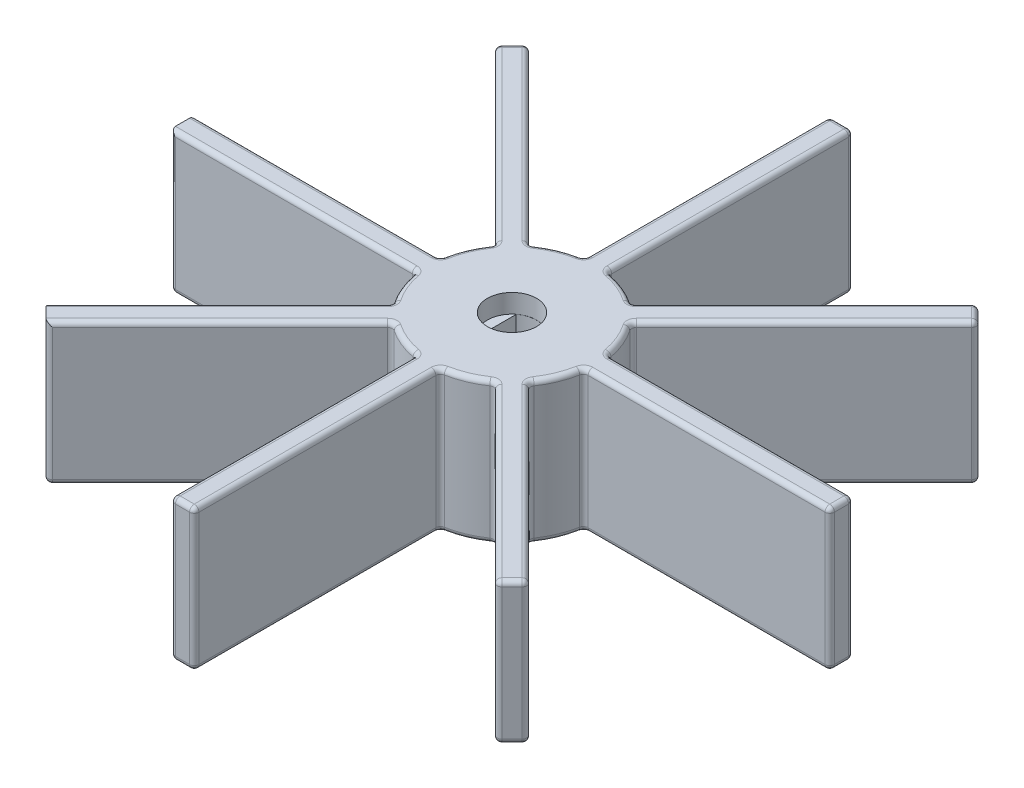
SolidWorks part; units mm, degrees
ref_plane "Front Plane" through (0, 0, 0) normal (0, 0, 1) x (1, 0, 0)
ref_plane "Top Plane" through (0, 0, 0) normal (0, 1, 0) x (1, 0, 0)
ref_plane "Right Plane" through (0, 0, 0) normal (1, 0, 0) x (0, 0, -1)
sketch "Sketch1" plane through (0, 0, 0) normal (0, 1, 0) x (1, 0, 0)
  line L0 (1.6, -2.0494) -> (1.6, 2.0494)
  line L1 (-1.6, -2.0494) -> (-1.6, 2.0494)
  line L2 (1.6, -2.0494) -> (-1.6, -2.0494) construction
  line L3 (1.6, 2.0494) -> (-1.6, 2.0494) construction
  circle A0 centre (0, 0) radius 9
  arc A1 (1.6, 2.0494) -> (-1.6, 2.0494) centre (0, 0) ccw
  arc A2 (-1.6, -2.0494) -> (1.6, -2.0494) centre (0, 0) ccw
  dimension "D1" = 18
  dimension "D2" = 5.2
  dimension "D3" = 3.2
extrude "Boss-Extrude1" add sketch "Sketch1" along normal blind 15
sketch "Sketch4" plane through (0, 0, 0) normal (0, 1, 0) x (1, 0, 0)
  line L0 (35, 0) -> (8, 0) construction
  line L2 (8, -1.25) -> (35, -1.25)
  line L3 (8, -1.25) -> (8, 1.25)
  line L4 (8, 1.25) -> (35, 1.25)
  line L5 (35, -1.25) -> (35, 1.25)
  dimension "D1" = 0
  dimension "D2" = 8
  dimension "D3" = 2.5
  dimension "D4" = 35
extrude "Boss-Extrude2" add sketch "Sketch4" along normal up to surface (15 mm away) up to face at (0, 15, 9)
pattern_circular "CirPattern1" count 8 over 360 about axis through (0, 0, 0) along (0, 1, 0) of "Boss-Extrude2"
sketch "Sketch6" plane through (0, 15, 0) normal (0, 1, 0) x (1, 0, 0)
  circle A0 centre (0, 0) radius 2.61
  dimension "D1" = 5.22
extrude "Cut-Extrude2" cut sketch "Sketch6" against normal blind 2
fillet "Fillet1" radius 0.5 98 edges at (-35, 7.5, -1.25) (-35, 0, 0) (-21.9564, 15, -1.25) (-21.9564, 15, 1.25) (-3.4442, 0, 8.3149) (-3.4442, 15, 8.3149) (-7.1862, 7.5, 5.4184) (-16.4094, 0, 14.6416) (-14.6416, 0, 16.4094) (-5.4184, 7.5, 7.1862) (-23.8649, 7.5, 25.6326) (-25.6326, 7.5, 23.8649) (-24.7487, 0, 24.7487) (-16.4094, 15, 14.6416) (-14.6416, 15, 16.4094) (3.4442, 0, 8.3149) (3.4442, 15, 8.3149) (-1.25, 7.5, 8.9128) (-1.25, 0, 21.9564) (1.25, 0, 21.9564) (1.25, 7.5, 8.9128) (1.25, 7.5, 35) (-1.25, 7.5, 35) (0, 0, 35) (-1.25, 15, 21.9564) (0, 15, 35) (1.25, 15, 21.9564) (8.3149, 0, 3.4442) (8.3149, 15, 3.4442) (5.4184, 7.5, 7.1862) (14.6416, 0, 16.4094) (16.4094, 0, 14.6416) (7.1862, 7.5, 5.4184) (25.6326, 7.5, 23.8649) (23.8649, 7.5, 25.6326) (24.7487, 0, 24.7487) (14.6416, 15, 16.4094) (24.7487, 15, 24.7487) (16.4094, 15, 14.6416) (8.3149, 15, -3.4442) (8.3149, 0, -3.4442) (8.9128, 7.5, -1.25) (8.9128, 7.5, 1.25) (21.9564, 0, 1.25) (21.9564, 0, -1.25) (35, 7.5, -1.25) (35, 7.5, 1.25) (35, 0, 0) (21.9564, 15, 1.25) (35, 15, 0) (21.9564, 15, -1.25) (3.4442, 0, -8.3149) (3.4442, 15, -8.3149) (7.1862, 7.5, -5.4184) (16.4094, 0, -14.6416) (14.6416, 0, -16.4094) (5.4184, 7.5, -7.1862) (23.8649, 7.5, -25.6326) (25.6326, 7.5, -23.8649) (24.7487, 0, -24.7487) (16.4094, 15, -14.6416) (24.7487, 15, -24.7487) (14.6416, 15, -16.4094) (-3.4442, 0, -8.3149) (-3.4442, 15, -8.3149) (1.25, 7.5, -8.9128) (1.25, 0, -21.9564) (-1.25, 0, -21.9564) (-1.25, 7.5, -8.9128) (-1.25, 7.5, -35) (1.25, 7.5, -35) (0, 0, -35) (1.25, 15, -21.9564) (0, 15, -35) (-1.25, 15, -21.9564) (-8.3149, 0, -3.4442) (0, 0, 2.6) (-8.3149, 15, -3.4442) (-5.4184, 7.5, -7.1862) (-14.6416, 0, -16.4094) (-16.4094, 0, -14.6416) (1.6, 0, 0) (-7.1862, 7.5, -5.4184) (-25.6326, 7.5, -23.8649) (-23.8649, 7.5, -25.6326) (-24.7487, 0, -24.7487) (-14.6416, 15, -16.4094) (-24.7487, 15, -24.7487) (-16.4094, 15, -14.6416) (0, 0, -2.6) (-1.6, 0, 0) (-8.3149, 0, 3.4442) (-8.3149, 15, 3.4442) (-8.9128, 7.5, -1.25) (-21.9564, 0, -1.25) (-21.9564, 0, 1.25) (-8.9128, 7.5, 1.25) (-35, 7.5, 1.25)
